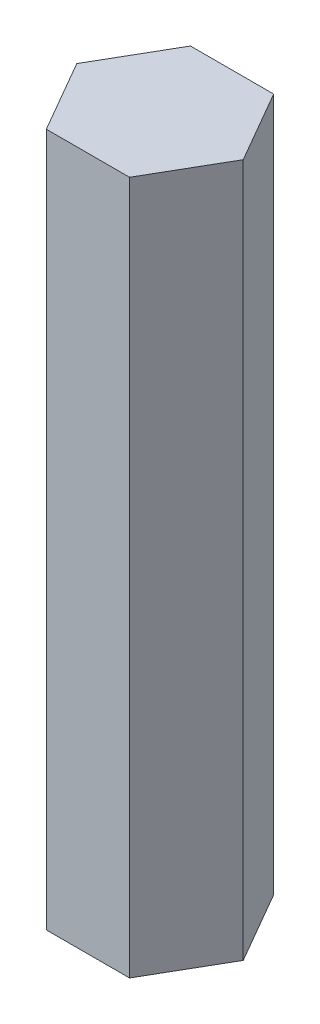
SolidWorks part; units mm, degrees
ref_plane "Front Plane" through (0, 0, 0) normal (0, 0, 1) x (1, 0, 0)
ref_plane "Top Plane" through (0, 0, 0) normal (0, 1, 0) x (1, 0, 0)
ref_plane "Right Plane" through (0, 0, 0) normal (1, 0, 0) x (0, 0, -1)
sketch "Sketch1" plane through (0, 0, 0) normal (0, 1, 0) x (1, 0, 0)
  line L1 (3, 0) -> (1.5, 2.5981)
  line L2 (1.5, 2.5981) -> (-1.5, 2.5981)
  line L3 (-1.5, 2.5981) -> (-3, 0)
  line L4 (-3, 0) -> (-1.5, -2.5981)
  line L5 (-1.5, -2.5981) -> (1.5, -2.5981)
  line L6 (1.5, -2.5981) -> (3, 0)
  circle A0 centre (0, 0) radius 2.5981 construction
  dimension "D1" = 3
extrude "Boss-Extrude1" add sketch "Sketch1" along normal blind 25
sketch "Sketch3" plane through (0, 0, 0) normal (0, -1, 0) x (1, 0, 0)
  circle A0 centre (0, 0) radius 1.6
  dimension "D1" = 3.2
extrude "Cut-Extrude1" cut sketch "Sketch3" against normal blind 5
